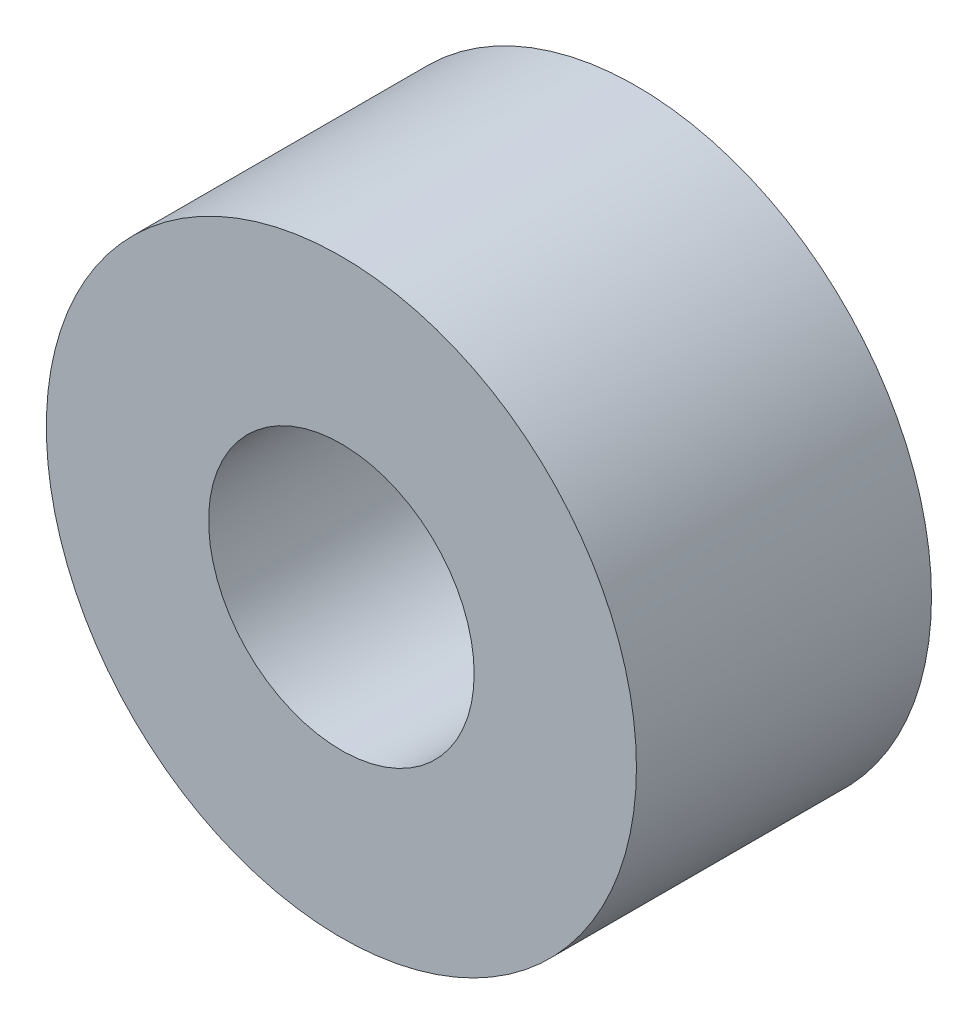
SolidWorks part; units mm, degrees
ref_plane "Front Plane" through (0, 0, 0) normal (0, 0, 1) x (1, 0, 0)
ref_plane "Top Plane" through (0, 0, 0) normal (0, 1, 0) x (1, 0, 0)
ref_plane "Right Plane" through (0, 0, 0) normal (1, 0, 0) x (0, 0, -1)
sketch "Sketch2" plane through (0, 0, 0) normal (0, 0, 1) x (1, 0, 0)
  circle A0 centre (0, 0) radius 5
  circle A1 centre (0, 0) radius 2.25
  dimension "D1" = 10
  dimension "D2" = 4.5
extrude "Boss-Extrude1" add sketch "Sketch2" along normal blind 5
